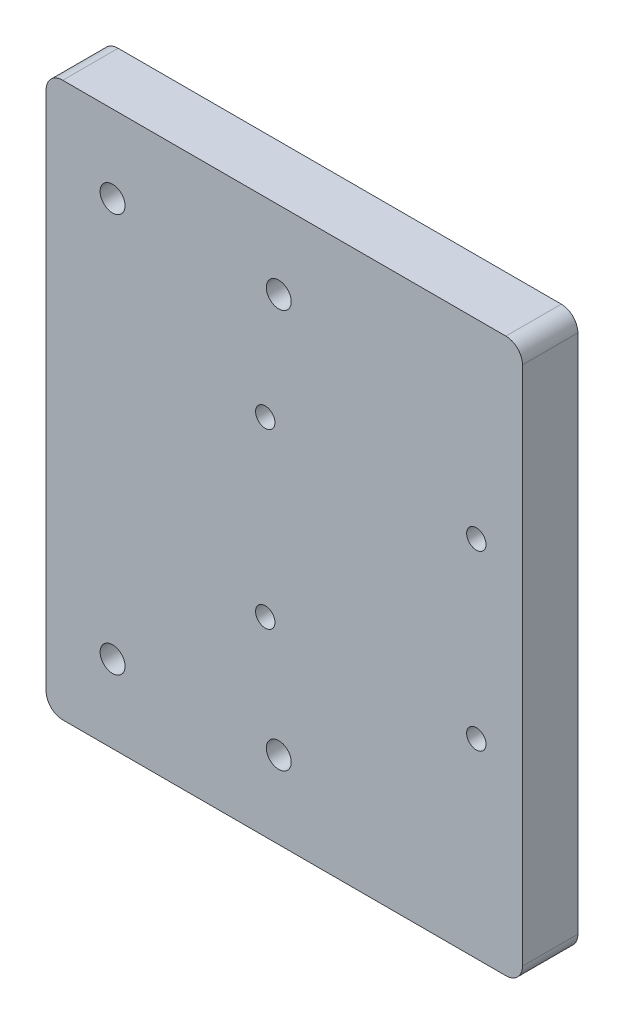
SolidWorks part; units mm, degrees
ref_plane "Front Plane" through (0, 0, 0) normal (0, 0, 1) x (1, 0, 0)
ref_plane "Top Plane" through (0, 0, 0) normal (0, 1, 0) x (1, 0, 0)
ref_plane "Right Plane" through (0, 0, 0) normal (1, 0, 0) x (0, 0, -1)
sketch "Sketch1" plane through (0, 0, 0) normal (0, 0, 1) x (1, 0, 0)
  line L0 (-43, -47) -> (-43, 47)
  line L1 (40, -50) -> (-40, -50)
  line L2 (-40, 50) -> (40, 50)
  line L3 (43, 47) -> (43, -47)
  arc A0 (-40, -50) -> (-43, -47) centre (-40, -47) cw
  arc A1 (-43, 47) -> (-40, 50) centre (-40, 47) cw
  arc A2 (43, -47) -> (40, -50) centre (40, -47) cw
  arc A3 (40, 50) -> (43, 47) centre (40, 47) cw
  circle A4 centre (-31, -36) radius 2.25
  circle A5 centre (-1, -36) radius 2.25
  circle A6 centre (-3.4375, -15.621) radius 1.75
  circle A7 centre (34.6625, -15.621) radius 1.75
  circle A8 centre (-3.4375, 15.621) radius 1.75
  circle A9 centre (-31, 36) radius 2.25
  circle A10 centre (-1, 36) radius 2.25
  circle A11 centre (34.6625, 15.621) radius 1.75
extrude "Plate_thickness" add sketch "Sketch1" along normal blind 10
